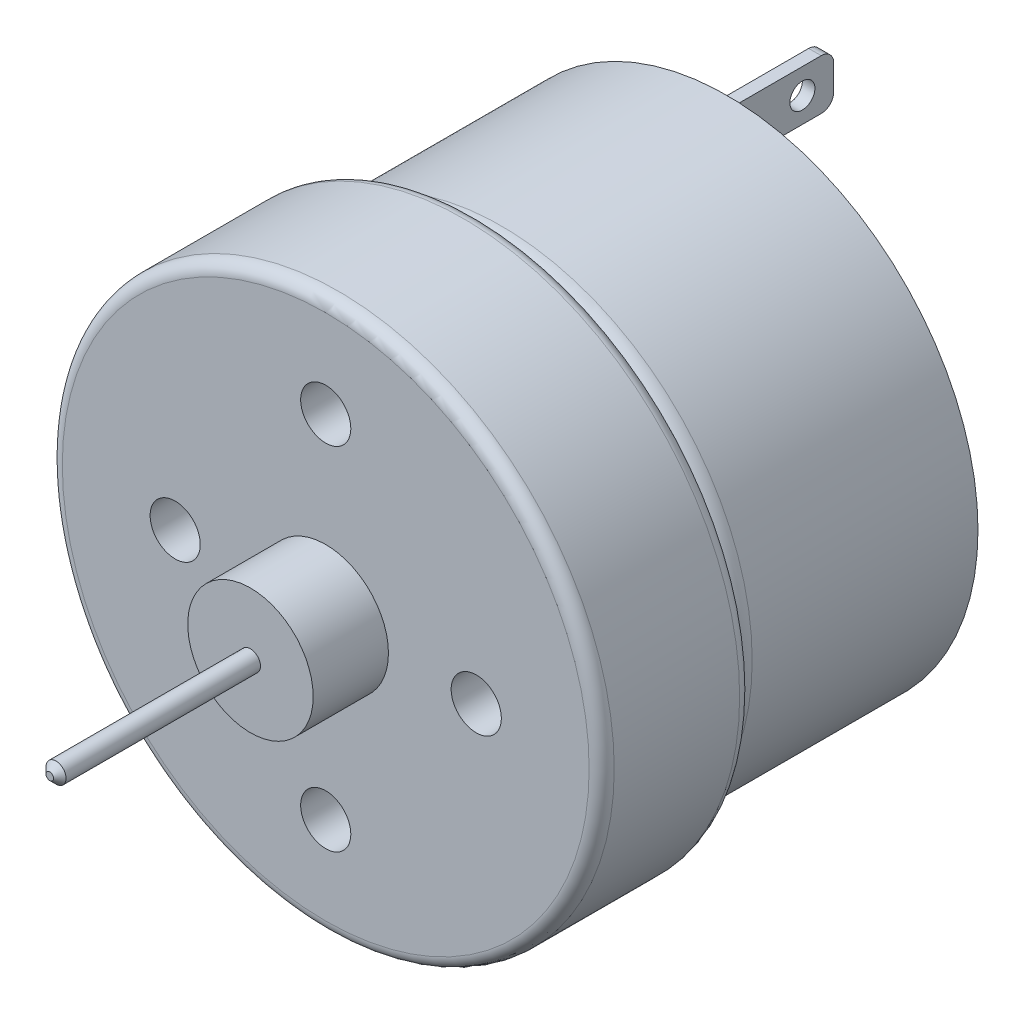
SolidWorks part; units mm, degrees
ref_plane "Front Plane" through (0, 0, 0) normal (0, 0, 1) x (1, 0, 0)
ref_plane "Top Plane" through (0, 0, 0) normal (0, 1, 0) x (1, 0, 0)
ref_plane "Right Plane" through (0, 0, 0) normal (1, 0, 0) x (0, 0, -1)
sketch "Sketch1" plane through (0, 0, 0) normal (0, 0, 1) x (1, 0, 0)
  circle A0 centre (0, 0) radius 10
  dimension "24.4" = 20
extrude "Boss-Extrude1" add sketch "Sketch1" along normal blind 10
fillet "Fillet1" radius 1 1 edges at (10, 0, 10)
sketch "Sketch2" plane through (0, 0, 0) normal (0, 0, -1) x (-1, 0, 0)
  circle A0 centre (0, 0) radius 3.25
  dimension "D1" = 6.5
extrude "Boss-Extrude2" add sketch "Sketch2" along normal blind 2
sketch "Sketch3" plane through (0, 0, 0) normal (0, 0, -1) x (-1, 0, 0)
  line L0 (0, 8.75) -> (0, -8.75)
  line L1 (8.3134, 0) -> (-8.3134, 0) construction
  line L3 (-0.25, 9.75) -> (0.25, 9.75)
  line L4 (-0.25, 9.75) -> (-0.25, 7.75)
  line L5 (-0.25, 7.75) -> (0.25, 7.75)
  line L6 (0.25, 9.75) -> (0.25, 7.75)
  line L7 (-0.25, 9.75) -> (0.25, 7.75) construction
  line L8 (-0.25, 7.75) -> (0.25, 9.75) construction
  point P4 (0, 0)
  point P8 (0, 0)
  dimension "D1" = 17.5
  dimension "D2" = 0.5
  dimension "D3" = 2
extrude "Boss-Extrude4" add sketch "Sketch3" along normal blind 4 contours L4 L5 L6 L3
sketch "Sketch5" plane through (-0.25, 0, 0) normal (-1, 0, 0) x (0, 0, 1)
  line L0 (-4, 8.75) -> (-2.75, 8.75)
  line L1 (-4, 9.75) -> (-4, 7.75) construction
  circle A0 centre (-2.75, 8.75) radius 0.5
  dimension "D2" = 1
  dimension "D1" = 1.25
extrude "Cut-Extrude2" cut sketch "Sketch5" against normal blind 4 contours A0
fillet "Fillet3" radius 0.5 2 edges at (0, 7.75, -4) (0, 9.75, -4)
mirror "Mirror2" about plane through (0, 0, 0) normal (0, 1, 0) of "Fillet3", "Cut-Extrude2", "Boss-Extrude4"
sketch "Sketch6" plane through (0, 0, 10) normal (0, 0, 1) x (1, 0, 0)
  circle A0 centre (0, 0) radius 11
  dimension "D1" = 22
extrude "Boss-Extrude5" add sketch "Sketch6" along normal blind 6
fillet "Fillet4" radius 0.5 2 edges at (11, 0, 16) (11, 0, 10)
sketch "Sketch7" plane through (0, 0, 16) normal (0, 0, 1) x (1, 0, 0)
  circle A0 centre (0, 0) radius 2.5
  dimension "D1" = 5
extrude "Boss-Extrude6" add sketch "Sketch7" along normal blind 3
sketch "Sketch8" plane through (0, 0, 19) normal (0, 0, 1) x (1, 0, 0)
  circle A0 centre (0, 0) radius 0.4
  dimension "D1" = 0.8
extrude "Boss-Extrude7" add sketch "Sketch8" along normal blind 8
chamfer "Chamfer1" distance 0.5 angle 45 1 edges at (-3.25, 0, -2)
chamfer "Chamfer2" distance 0.25 angle 45 1 edges at (0.4, 0, 27)
sketch "Sketch16" plane through (0, 0, 16) normal (0, 0, 1) x (1, 0, 0)
  line L0 (0, 0) -> (0, 10.5) construction
  line L1 (0, 0) -> (0, -10.5) construction
  line L2 (0, 0) -> (-10.5, 0) construction
  line L3 (0, 0) -> (10.5, 0) construction
  circle A0 centre (0, 0) radius 10.5 construction
  circle A1 centre (0, 7) radius 1
  circle A2 centre (0, -7) radius 1
  circle A3 centre (6, 0) radius 1
  circle A4 centre (-6, 0) radius 1
  dimension "D3" = 6
  dimension "D1" = 7
  dimension "D2" = 7
extrude "Cut-Extrude3" cut sketch "Sketch16" against normal blind 8
